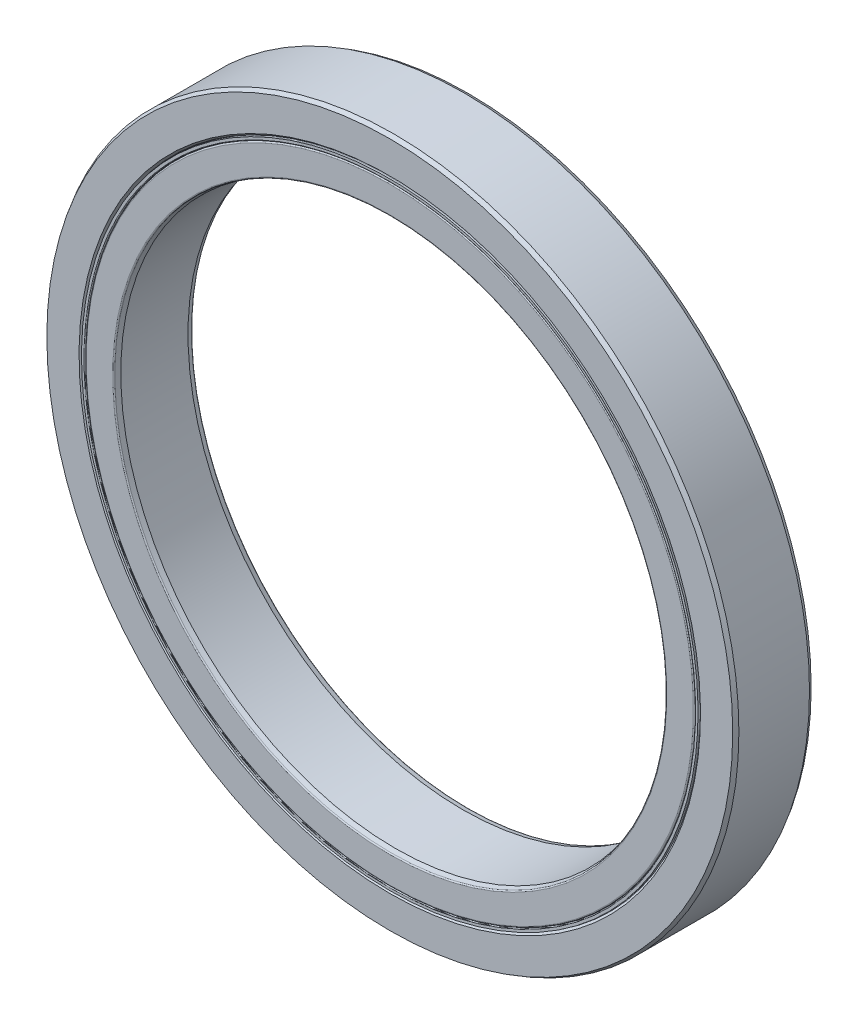
SolidWorks part; units mm, degrees
ref_plane "Front Plane" through (0, 0, 0) normal (0, 0, 1) x (1, 0, 0)
ref_plane "Top Plane" through (0, 0, 0) normal (0, 1, 0) x (1, 0, 0)
ref_plane "Right Plane" through (0, 0, 0) normal (1, 0, 0) x (0, 0, -1)
sketch "Sketch1" plane through (0, 0, 0) normal (0, 0, 1) x (1, 0, 0)
  line L0 (-22, 0) -> (22, 0) construction
  line L1 (-17.5, 0) -> (17.5, 0) construction
  circle A0 centre (0, 0) radius 17.5 construction
  circle A1 centre (0, 0) radius 22 construction
  point P3 (0, 0)
  point P6 (0, 0)
  point P7 (0, -17.5)
  point P11 (0, -22)
  point P12 (0, 17.5)
  point P13 (0, 22)
  dimension "OD" = 44
  dimension "ID" = 35
sketch "Sketch2" plane through (0, 0, 0) normal (1, 0, 0) x (0, 0, -1)
  line L0 (-2.5, 22) -> (2.5, 22) construction
  line L1 (0, 22) -> (0, -22) construction
  line L2 (2.25, 22) -> (-2.25, 22)
  line L3 (-2.25, 22) -> (-2.5, 21.8557)
  line L4 (-2.5, 21.8557) -> (-2.5, 19.8037)
  line L5 (-2.1037, 19.58) -> (-1.6859, 19.58)
  line L6 (2.1037, 19.58) -> (1.6859, 19.58)
  line L7 (2.5, 21.8557) -> (2.5, 19.8037)
  line L8 (2.25, 22) -> (2.5, 21.8557)
  line L9 (-1.6859, 19.58) -> (-1.6859, 20.3867) construction
  line L10 (-1.6859, 20.3867) -> (-1.6859, 21.1933) construction
  line L11 (0, 22) -> (0, -22) construction
  line L12 (-2.5, 0) -> (2.5, 0) construction
  line L13 (2.5, 17.5) -> (-2.5, 17.5) construction
  line L14 (-2.5, 17.5) -> (-2.5, -17.5) construction
  line L15 (-2.5, -17.5) -> (2.5, -17.5) construction
  line L16 (2.5, 22) -> (2.5, -22) construction
  line L17 (-1.6859, 21.1933) -> (-1.6859, 22) construction
  line L18 (-1.6859, 21.1933) -> (0, 21.1933) construction
  line L20 (-2.1037, 19.58) -> (-2.375, 19.6787)
  line L21 (-2.375, 19.6787) -> (-2.5, 19.8037)
  line L26 (2.375, 19.6787) -> (2.5, 19.8037)
  line L27 (2.1037, 19.58) -> (2.375, 19.6787)
  arc A0 (-1.6859, 19.58) -> (1.6859, 19.58) centre (0, 19.5058) cw
  circle A1 centre (0, 19.5058) radius 1.6875 construction
  point P17 (0, 0)
  point P21 (0, 22)
  point P30 (0, -17.5)
  dimension "Approx. Ball Dia." = 3.375
  dimension "Width" = 5
  dimension "For Shaft Diameter" = 35
  dimension "For Housing ID" = 44
  dimension "D4" = 39.16
  dimension "D2" = 20
  dimension "D5" = 45
  dimension "D1" = 30
  dimension "D6" = 0.25
  dimension "D7" = 0.125
sketch "Sketch3" plane through (0, 0, 0) normal (1, 0, 0) x (0, 0, -1)
  line L14 (-2.1037, 19.58) -> (-2.375, 19.6787) construction
  line L15 (-2.375, 19.6787) -> (-2.5, 19.8037) construction
  line L16 (-2.5, 21.8557) -> (-2.5, 19.8037) construction
  line L17 (-2.25, 22) -> (-2.5, 21.8557) construction
  line L18 (2.25, 22) -> (-2.25, 22) construction
  line L19 (2.25, 22) -> (2.5, 21.8557) construction
  line L20 (2.5, 21.8557) -> (2.5, 19.8037) construction
  line L21 (2.375, 19.6787) -> (2.5, 19.8037) construction
  line L22 (2.1037, 19.58) -> (2.375, 19.6787) construction
  line L23 (2.1037, 19.58) -> (1.6859, 19.58) construction
  line L24 (-2.1037, 19.58) -> (-1.6859, 19.58) construction
  line L25 (-2.1037, 19.58) -> (-2.375, 19.6787)
  line L26 (-2.375, 19.6787) -> (-2.5, 19.8037)
  line L27 (-2.5, 21.8557) -> (-2.5, 19.8037)
  line L28 (-2.25, 22) -> (-2.5, 21.8557)
  line L29 (2.25, 22) -> (-2.25, 22)
  line L30 (2.25, 22) -> (2.5, 21.8557)
  line L31 (2.5, 21.8557) -> (2.5, 19.8037)
  line L32 (2.375, 19.6787) -> (2.5, 19.8037)
  line L33 (2.1037, 19.58) -> (2.375, 19.6787)
  line L34 (2.1037, 19.58) -> (1.6859, 19.58)
  line L35 (-2.1037, 19.58) -> (-1.6859, 19.58)
  arc A2 (1.6859, 19.58) -> (-1.6859, 19.58) centre (0, 19.5058) ccw construction
  arc A3 (1.6859, 19.58) -> (-1.6859, 19.58) centre (0, 19.5058) ccw
revolve "Revolve1" add sketch "Sketch3" angle 360 about L12
sketch "Sketch4" plane through (0, 0, 0) normal (1, 0, 0) x (0, 0, -1)
  line L0 (0, 22) -> (0, -22) construction
  line L1 (0, 22) -> (0, -22) construction
  line L2 (-2.1419, 17.5) -> (-2.4389, 17.5796)
  line L3 (-2.5, 17.6592) -> (-2.5, 19.3493)
  line L4 (2.5, -21.8557) -> (2.5, 21.8557) construction
  line L5 (-2.4176, 19.4317) -> (-1.6859, 19.4317)
  line L6 (-2.1419, 17.5) -> (2.1419, 17.5)
  line L7 (2.5, 21.8557) -> (2.5, 19.8037) construction
  line L8 (2.1419, 17.5) -> (2.4389, 17.5796)
  line L9 (0, 21.1933) -> (0, 17.5) construction
  line L10 (2.5, 17.6592) -> (2.5, 19.3493)
  line L11 (2.4176, 19.4317) -> (1.6859, 19.4317)
  line L12 (2.1419, 17.5) -> (2.1419, 17.5796) construction
  line L13 (2.1419, 17.5796) -> (2.1419, 17.6592) construction
  line L14 (2.1419, 17.6592) -> (2.1419, 17.7387) construction
  line L15 (2.1419, 17.7387) -> (2.1419, 17.8183) construction
  circle A0 centre (0, 19.5058) radius 1.6875 construction
  arc A1 (1.6859, 19.4317) -> (-1.6859, 19.4317) centre (0, 19.5058) cw
  arc A2 (2.5, 19.3493) -> (2.4176, 19.4317) centre (2.4176, 19.3493) ccw
  arc A3 (-2.5, 19.3493) -> (-2.4176, 19.4317) centre (-2.4176, 19.3493) cw
  arc A4 (2.4389, 17.5796) -> (2.5, 17.6592) centre (2.4176, 17.6592) ccw
  arc A5 (-2.4389, 17.5796) -> (-2.5, 17.6592) centre (-2.4176, 17.6592) cw
  point P14 (2.5, 17.5959)
  point P36 (0, 17.8183)
  dimension "D1" = 15
revolve "Revolve2" add sketch "Sketch4" angle 360 about L12
sketch "Sketch5" plane through (0, 0, 0) normal (1, 0, 0) x (0, 0, -1)
  line L0 (-1.6875, 19.5058) -> (1.6875, 19.5058)
  arc A2 (-1.6875, 19.5058) -> (1.6875, 19.5058) centre (0, 19.5058) cw
  arc A3 (1.6859, 19.58) -> (-1.6859, 19.58) centre (0, 19.5058) ccw construction
revolve "Revolve3" add sketch "Sketch5" angle 360 about L0
pattern_circular "CirPattern1" count 23 over 360 about axis through (0, 0, 0) along (0, 0, 1) of bodies 104
sketch "Sketch6" plane through (0, 0, 0) normal (1, 0, 0) x (0, 0, -1)
  line L1 (-2.3441, 19.58) -> (-1.6875, 19.58)
  line L2 (-2.5, 19.49) -> (-2.5, 19.6477)
  line L3 (-2.464, 19.6117) -> (-1.6875, 19.6117)
  line L4 (-1.6875, 19.58) -> (-1.6875, 19.6117)
  line L5 (-2.5, 17.6592) -> (-2.5, 19.3493) construction
  line L6 (-2.25, 22) -> (-2.5, 21.8557) construction
  line L7 (0, 22) -> (0, 17.5) construction
  line L8 (2.464, 19.6117) -> (1.6875, 19.6117)
  line L9 (1.6875, 19.58) -> (1.6875, 19.6117)
  line L10 (2.3441, 19.58) -> (1.6875, 19.58)
  line L11 (2.5, 19.49) -> (2.5, 19.6477)
  line L13 (-2.4176, 19.4317) -> (-1.6859, 19.4317) construction
  line L14 (-2.5, 19.49) -> (-2.3441, 19.58)
  line L15 (-2.1037, 19.58) -> (-1.6859, 19.58) construction
  line L16 (2.5, 19.49) -> (2.3441, 19.58)
  arc A0 (-2.5, 19.6477) -> (-2.464, 19.6117) centre (-2.464, 19.6477) ccw
  circle A1 centre (0, 19.5058) radius 1.6875 construction
  arc A2 (2.5, 19.6477) -> (2.464, 19.6117) centre (2.464, 19.6477) cw
  point P26 (-2.5, 19.6117)
  dimension "D3" = 0.036
  dimension "D1" = 0.18
  dimension "D2" = 0.09
revolve "Revolve4" add sketch "Sketch6" angle 360 about L12
sketch "Sketch7" plane through (0, 0, 0) normal (1, 0, 0) x (0, 0, -1)
  line L3 (-1.6875, 19.6117) -> (-2.3664, 19.6117)
  line L4 (-2.464, 19.6117) -> (-1.6875, 19.6117) construction
  line L7 (0, 17.8183) -> (0, 17.5) construction
  line L8 (0, 22) -> (0, -22) construction
  line L21 (-2.3664, 19.6117) -> (-2.4108, 19.6039)
  line L22 (-2.4075, 19.5667) -> (-2.4325, 19.5667)
  line L23 (-2.4325, 19.4317) -> (-1.6875, 19.4317)
  line L24 (-1.6875, 19.4317) -> (-1.6875, 19.6117)
  line L25 (-2.4176, 19.4317) -> (-1.6859, 19.4317) construction
  line L26 (-2.5, 19.6477) -> (-2.5, 19.4317) construction
  line L27 (-2.5, 19.4317) -> (-2.4325, 19.4317) construction
  line L28 (-2.3664, 19.6117) -> (-2.3664, 19.5667) construction
  line L29 (-2.3664, 19.5667) -> (-2.3664, 19.5217) construction
  line L30 (-2.3664, 19.5217) -> (-2.3664, 19.4767) construction
  line L31 (-2.3664, 19.4767) -> (-2.3664, 19.4317) construction
  circle A2 centre (0, 19.5058) radius 1.6875 construction
  arc A9 (-2.4108, 19.6039) -> (-2.4075, 19.5667) centre (-2.4075, 19.5854) ccw
  arc A10 (-2.4325, 19.5667) -> (-2.4325, 19.4317) centre (-2.4325, 19.4992) ccw
  dimension "D1" = 0.025
  dimension "D2" = 10
revolve "Revolve5" add sketch "Sketch7" angle 360 about L12
equation "\"D4@Sketch2\"=\"OD@Sketch1\"*.89"
equation "\"D1@Sketch6\"=(\"OD@Sketch1\"-\"ID@Sketch1\")*.02"
equation "\"D2@Sketch6\"=\"D1@Sketch6\"*.5"
equation "\"D3@Sketch6\"=\"D1@Sketch6\"*.2"
equation "\"D6@Sketch2\"=\"Width@Sketch2\"*.05"
equation "\"D7@Sketch2\"=\"D6@Sketch2\"*.5"
equation "\"D1@CirPattern1\" =  ( pi * \"OD@Sketch1\" )  * .5625 / \"Approx. Ball Dia.@Sketch2\""
equation "\"Approx. Ball Dia.@Sketch2\"=(\"OD@Sketch1\"-\"ID@Sketch1\")*.5*.75"
